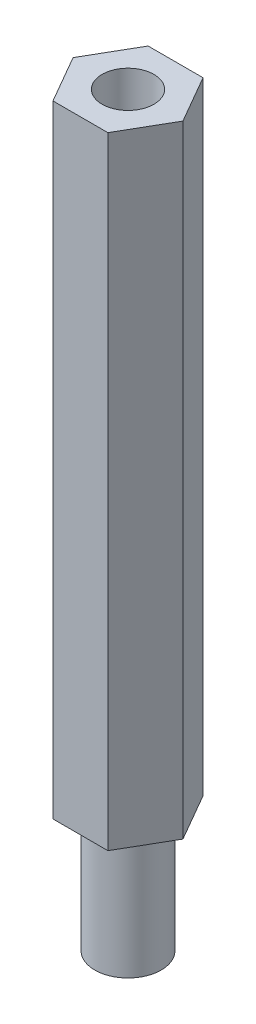
SolidWorks part; units mm, degrees
ref_plane "前视基准面" through (0, 0, 0) normal (0, 0, 1) x (1, 0, 0)
ref_plane "上视基准面" through (0, 0, 0) normal (0, 1, 0) x (1, 0, 0)
ref_plane "右视基准面" through (0, 0, 0) normal (1, 0, 0) x (0, 0, -1)
sketch "草图4" plane through (0, 0, 0) normal (0, 1, 0) x (1, 0, 0)
  line L0 (-12.7945, 0) -> (16.3015, 0) construction
  line L2 (1.325, -2.295) -> (2.65, 0)
  line L3 (2.65, 0) -> (1.325, 2.295)
  line L4 (1.325, 2.295) -> (-1.325, 2.295)
  line L5 (-1.325, 2.295) -> (-2.65, 0)
  line L6 (-2.65, 0) -> (-1.325, -2.295)
  line L7 (-1.325, -2.295) -> (1.325, -2.295)
  circle A0 centre (0, 0) radius 2.295 construction
  dimension "D1" = 5.3
extrude "凸台-拉伸1" add sketch "草图4" along normal blind 30
sketch "草图6" plane through (0, 0, 0) normal (0, -1, 0) x (-1, 0, 0)
  circle A0 centre (0, 0) radius 1.6
  dimension "D1" = 3.2
extrude "凸台-拉伸2" add sketch "草图6" along normal blind 6
cosmetic thread "装饰螺纹线1" parameters "D2"=2.5
sketch "草图7" plane through (0, 30, 0) normal (0, 1, 0) x (1, 0, 0)
  circle A0 centre (0, 0) radius 1.25
  dimension "D1" = 2.5
extrude "切除-拉伸1" cut sketch "草图7" against normal blind 5
cosmetic thread "装饰螺纹线2" parameters "D2"=3
